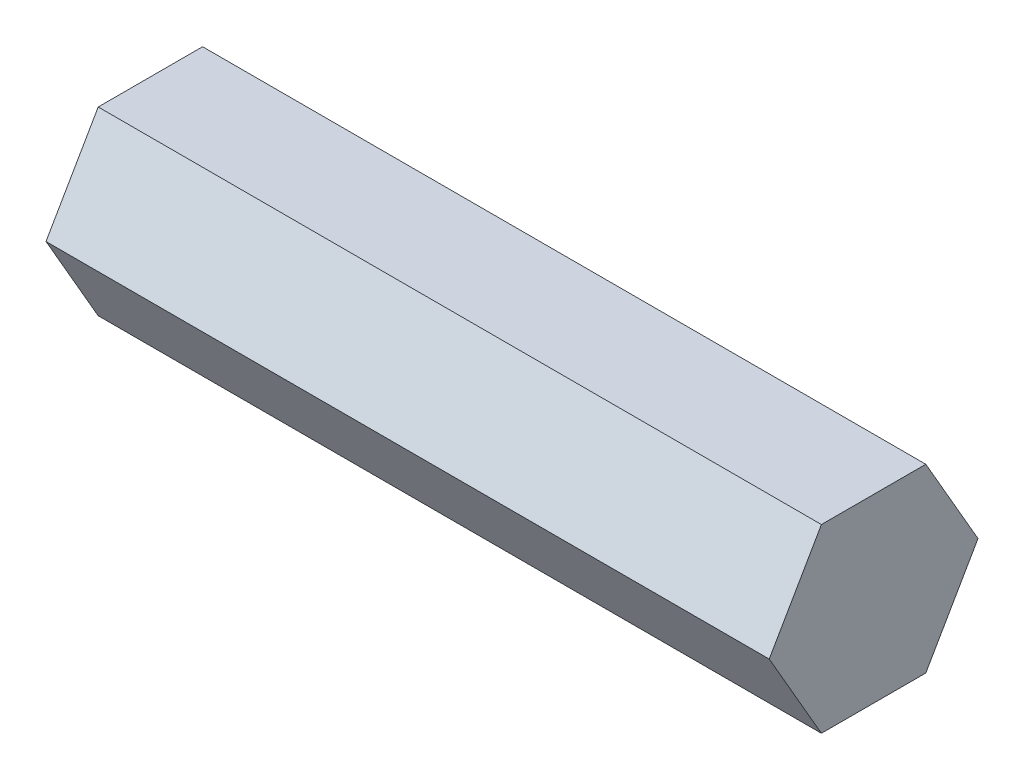
SolidWorks part; units mm, degrees
ref_plane "Front Plane" through (0, 0, 0) normal (0, 0, 1) x (1, 0, 0)
ref_plane "Top Plane" through (0, 0, 0) normal (0, 1, 0) x (1, 0, 0)
ref_plane "Right Plane" through (0, 0, 0) normal (1, 0, 0) x (0, 0, -1)
sketch "Sketch1" plane through (0, 0, 0) normal (1, 0, 0) x (0, 0, -1)
  line L1 (7.3323, 0) -> (3.6662, 6.35)
  line L2 (3.6662, 6.35) -> (-3.6662, 6.35)
  line L3 (-3.6662, 6.35) -> (-7.3323, 0)
  line L4 (-7.3323, 0) -> (-3.6662, -6.35)
  line L5 (-3.6662, -6.35) -> (3.6662, -6.35)
  line L6 (3.6662, -6.35) -> (7.3323, 0)
  circle A0 centre (0, 0) radius 6.35 construction
  dimension "D1" = 12.7
extrude "Boss-Extrude1" add sketch "Sketch1" along normal blind 50.8
